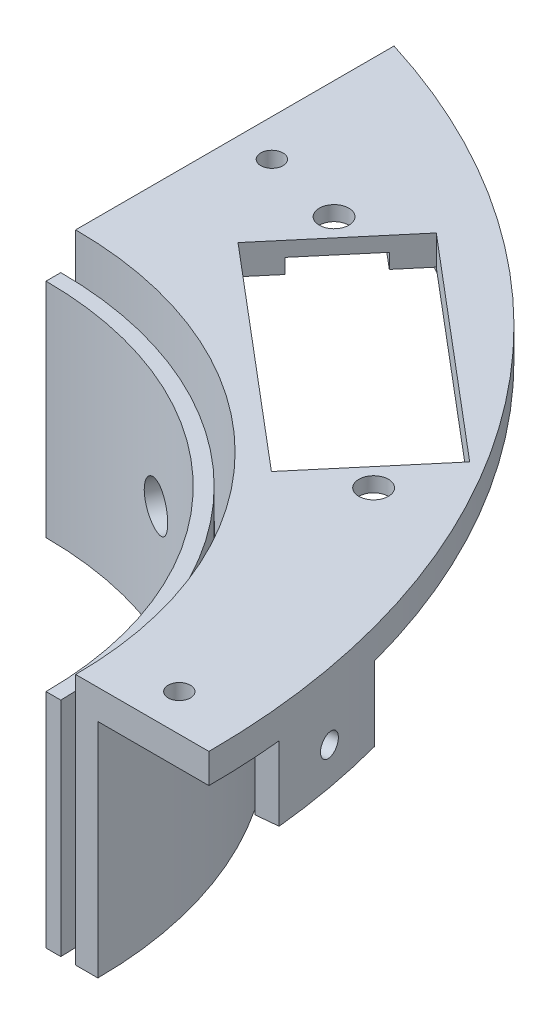
SolidWorks part; units mm, degrees
ref_plane "Front Plane" through (0, 0, 0) normal (0, 0, 1) x (1, 0, 0)
ref_plane "Top Plane" through (0, 0, 0) normal (0, 1, 0) x (1, 0, 0)
ref_plane "Right Plane" through (0, 0, 0) normal (1, 0, 0) x (0, 0, -1)
sketch "Sketch1" plane through (0, 0, 0) normal (0, 1, 0) x (1, 0, 0)
  line L0 (0, 0) -> (0, 2)
  line L1 (48, -48) -> (50, -48)
  line L2 (0, -48) -> (19.5959, -2) construction
  line L3 (0, -48) -> (46, -28.4041) construction
  arc A0 (0, 2) -> (50, -48) centre (0, -48) cw
  arc A1 (0, 0) -> (48, -48) centre (0, -48) cw
  dimension "D1" = 50
  dimension "D2" = 2
  dimension "D3" = 2
  dimension "D4" = 50
  dimension "D5" = 20
  dimension "D7" = 20
extrude "Boss-Extrude1" add sketch "Sketch1" along normal mid plane 30
ref_plane "Plane1" through (19.5959, 0, 2) normal (0.3919, 0, -0.92) x (-0.92, 0, -0.3919)
sketch "Sketch2" plane through (19.5959, 0, 2) normal (0.3919, 0, -0.92) x (-0.92, 0, -0.3919)
  line L0 (18.8121, 0) -> (-44.16, 0) construction
  circle A0 centre (0, 0) radius 5.6
  dimension "D1" = 11.2
sketch "Sketch3" plane through (0, 0, 0) normal (0, 1, 0) x (1, 0, 0)
  line L0 (0, 4) -> (0, 7)
  line L1 (52, -48) -> (55, -48)
  line L2 (48, -48) -> (50, -48) construction
  arc A0 (0, 4) -> (52, -48) centre (0, -48) cw
  arc A1 (0, 7) -> (55, -48) centre (0, -48) cw
  dimension "D1" = 3
  dimension "D2" = 2
  dimension "D3" = 2
  dimension "D4" = 3
extrude "Boss-Extrude3" add sketch "Sketch3" along normal mid plane 30 separate body
extrude "Boss-Extrude4" add sketch "Sketch2" along normal up to surface and the other way up to surface up to face at (31.3848, 0, 16.6152) other way up to face at (30.1777, 0, 17.8223)
ref_plane "Plane2" through (46, 0, 28.4041) normal (0.92, 0, -0.3919) x (-0.3919, 0, -0.92)
sketch "Sketch4" plane through (46, 0, 28.4041) normal (0.92, 0, -0.3919) x (-0.3919, 0, -0.92)
  circle A0 centre (0, 0) radius 5.6
  dimension "D1" = 11.2
extrude "Boss-Extrude5" add sketch "Sketch4" along normal up to surface and the other way up to surface up to face at (31.3848, 0, 16.6152) other way up to face at (30.1777, 0, 17.8223)
sketch "Sketch5" plane through (19.5959, 0, 2) normal (0.3919, 0, -0.92) x (-0.92, 0, -0.3919)
  circle A0 centre (0, 0) radius 1.5
  dimension "D1" = 3
extrude "Cut-Extrude1" cut sketch "Sketch5" against normal through all and the other way through all
sketch "Sketch6" plane through (19.5959, 0, 2) normal (0.3919, 0, -0.92) x (-0.92, 0, -0.3919)
  circle A0 centre (0, 0) radius 3
  dimension "D1" = 6
extrude "Cut-Extrude2" cut sketch "Sketch6" against normal through all
sketch "Sketch7" plane through (46, 0, 28.4041) normal (0.92, 0, -0.3919) x (-0.3919, 0, -0.92)
  circle A0 centre (0, 0) radius 1.5
  dimension "D1" = 3
extrude "Cut-Extrude3" cut sketch "Sketch7" against normal through all both and the other way through all
sketch "Sketch8" plane through (46, 0, 28.4041) normal (0.92, 0, -0.3919) x (-0.3919, 0, -0.92)
  circle A0 centre (0, 0) radius 3
  dimension "D1" = 6
extrude "Cut-Extrude4" cut sketch "Sketch8" against normal through all
sketch "Sketch9" plane through (0, 15, 0) normal (0, 1, 0) x (1, 0, 0)
  line L0 (0, 4) -> (0, 47)
  line L1 (52, -48) -> (70, -48)
  line L2 (70, -48) -> (70, 47) construction
  line L3 (70, 47) -> (0, 47) construction
  arc A1 (0, 4) -> (52, -48) centre (0, -48) cw
  arc A2 (52, -48) -> (0, 4) centre (0, -48) ccw construction
  arc A3 (0, 47) -> (70, -48) centre (-29.4643, -48) cw
  dimension "D1" = 40
  dimension "D2" = 15
extrude "Boss-Extrude6" add sketch "Sketch9" along normal blind 4
sketch "Sketch10" plane through (0, 19, 0) normal (0, 1, 0) x (1, 0, 0)
  line L0 (34.7149, 27.988) -> (24.7149, 27.988) construction
  line L7 (34.7149, 27.988) -> (57.9093, 8.398) construction
  line L8 (57.9093, 8.398) -> (53.7459, 3.4685) construction
  line L9 (12.4552, 13.4725) -> (41.4862, -11.047)
  line L10 (41.4862, -11.047) -> (53.7459, 3.4685)
  line L11 (53.7459, 3.4685) -> (24.7149, 27.988)
  line L12 (24.7149, 27.988) -> (12.4552, 13.4725)
  arc A3 (55, -48) -> (0, 7) centre (0, -48) ccw construction
  arc A4 (70, -48) -> (0, 47) centre (-29.4643, -48) ccw construction
  dimension "D1" = 38
  dimension "D2" = 19
  dimension "D3" = 10
extrude "Cut-Extrude5" cut sketch "Sketch10" against normal up to surface (4 mm away) up to face at (38.0002, 15, 4.7768)
sketch "Sketch12" plane through (0, 19, 0) normal (0, 1, 0) x (1, 0, 0)
  line L0 (18.5851, 20.7302) -> (47.616, -3.7892) construction
  line L3 (15.9112, 22.9886) -> (18.5851, 20.7302) construction
  line L4 (47.616, -3.7892) -> (50.2899, -6.0476) construction
  line L5 (0, 25.5) -> (5, 25.5) construction
  line L7 (61, -43) -> (61, -48) construction
  line L9 (41.4862, -11.047) -> (53.7459, 3.4685) construction
  line L10 (24.7149, 27.988) -> (12.4552, 13.4725) construction
  line L11 (52, -48) -> (70, -48) construction
  line L12 (0, 47) -> (0, 4) construction
  circle A0 centre (15.9112, 22.9886) radius 2
  circle A1 centre (50.2899, -6.0476) radius 2
  circle A2 centre (5, 25.5) radius 1.5
  circle A3 centre (61, -43) radius 1.5
  dimension "D1" = 4
  dimension "D2" = 4
  dimension "D4" = 3
  dimension "D3" = 3.5
  dimension "D5" = 5
extrude "Cut-Extrude6" cut sketch "Sketch12" against normal through all
sketch "Sketch13" plane through (0, 19, 0) normal (0, 1, 0) x (-1, 0, 0)
  line L0 (-15.3588, -16.9104) -> (-7.7191, -23.3629)
  line L1 (-24.7149, -27.988) -> (-12.4552, -13.4725) construction
  line L2 (-7.7191, -23.3629) -> (-14.1716, -31.0026)
  line L3 (-14.1716, -31.0026) -> (-21.8113, -24.5501)
  line L4 (-21.8113, -24.5501) -> (-15.3588, -16.9104)
  line L5 (-18.5851, -20.7302) -> (-10.9453, -27.1827) construction
  line L6 (-12.4552, -13.4725) -> (-15.3588, -16.9104) construction
  line L7 (-21.8113, -24.5501) -> (-24.7149, -27.988) construction
  line L8 (-4.3744, 25.5412) -> (-39.2304, -15.7282) construction
  line L10 (-53.7459, -3.4685) -> (-24.7149, -27.988) construction
  line L11 (-58.482, 6.4218) -> (-50.8423, -0.0306)
  line L12 (-52.0295, 14.0616) -> (-58.482, 6.4218)
  line L13 (-44.3898, 7.6091) -> (-52.0295, 14.0616)
  line L14 (-50.8423, -0.0306) -> (-44.3898, 7.6091)
  dimension "D1" = 10
  dimension "D2" = 10
extrude "Cut-Extrude7" cut sketch "Sketch13" along normal offset from surface (2 mm away) 2 from surface at -4 up to face at (61, 19, 44.5) starting at face at (61, 15, 41.5)
sketch "Sketch15" plane through (19.5959, 0, 2) normal (0.3919, 0, -0.92) x (-0.92, 0, -0.3919)
  circle A0 centre (0, 0) radius 1.5
  circle A1 centre (0, 0) radius 1.5 construction
extrude "Cut-Extrude8" cut sketch "Sketch15" along normal through all
sketch "Sketch17" plane through (46, 0, 28.4041) normal (0.92, 0, -0.3919) x (-0.3919, 0, -0.92)
  circle A0 centre (0, 0) radius 1.5
  circle A1 centre (0, 0) radius 1.5 construction
extrude "Cut-Extrude9" cut sketch "Sketch17" along normal through all
sketch "Sketch19" plane through (0, 15, 0) normal (0, 1, 0) x (-1, 0, 0)
  line L0 (-66.6155, 22.2743) -> (-63.7176, 23.0502)
  line L2 (-21.9689, -33.6087) -> (-23.5685, -36.1467)
  line L3 (-69.4973, 38.0126) -> (-66.5125, 38.3139)
  line L4 (-8.2183, -40.7997) -> (-9.3902, -43.5613)
  line L5 (29.4643, 48) -> (-63.7176, 23.0502) construction
  line L6 (-21.9689, -33.6087) -> (29.4643, 48) construction
  arc A0 (-66.6155, 22.2743) -> (-69.4973, 38.0126) centre (29.4643, 48) cw
  arc A1 (-70, 48) -> (0, -47) centre (29.4643, 48) ccw construction
  arc A2 (-63.7176, 23.0502) -> (-66.5125, 38.3139) centre (29.4643, 48) cw
  arc A3 (-8.2183, -40.7997) -> (-21.9689, -33.6087) centre (29.4643, 48) cw
  arc A4 (-9.3902, -43.5613) -> (-23.5685, -36.1467) centre (29.4643, 48) cw
  arc A5 (-70, 48) -> (0, -47) centre (29.4643, 48) ccw construction
  dimension "D1" = 10
  dimension "D2" = 3
  dimension "D3" = 16
  dimension "D4" = 16
  dimension "D5" = 10
  dimension "D6" = 3
extrude "Boss-Extrude7" add sketch "Sketch19" against normal blind 10
sketch "Sketch20" plane through (0, 5, 0) normal (0, -1, 0) x (1, 0, 0)
  line L0 (68.3734, 30.0854) -> (-29.4643, 48) construction
  line L1 (-29.4643, 48) -> (16.6287, -40.1396) construction
  arc A0 (66.6155, 22.2743) -> (69.4973, 38.0126) centre (-29.4643, 48) ccw construction
  arc A1 (9.3902, -43.5613) -> (23.5685, -36.1467) centre (-29.4643, 48) ccw construction
ref_plane "Plane3" through (16.6287, 5, -40.1396) normal (0.4634, 0, -0.8861) x (-0.8861, 0, -0.4634)
sketch "Sketch21" plane through (16.6287, 5, -40.1396) normal (0.4634, 0, -0.8861) x (-0.8861, 0, -0.4634)
  line L0 (-8, 10) -> (8, 0) construction
  circle A0 centre (0, 5) radius 1.5
  dimension "D1" = 3
extrude "Cut-Extrude10" cut sketch "Sketch21" against normal up to surface (3.0117 mm away)
ref_plane "Plane4" through (68.3734, 5, 30.0854) normal (0.9836, 0, -0.1801) x (-0.1801, 0, -0.9836)
sketch "Sketch22" plane through (68.3734, 5, 30.0854) normal (0.9836, 0, -0.1801) x (-0.1801, 0, -0.9836)
  line L0 (-8, 10) -> (8, 0) construction
  circle A0 centre (0, 5) radius 1.5
  dimension "D1" = 3
extrude "Cut-Extrude11" cut sketch "Sketch22" against normal up to surface (3.0117 mm away)
